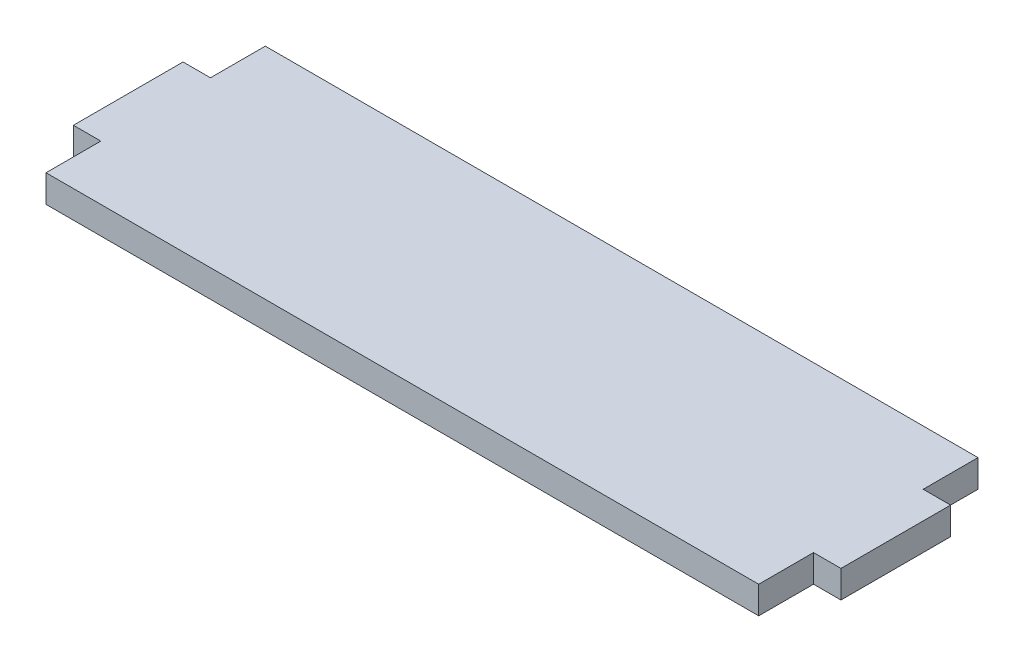
SolidWorks part; units mm, degrees
material "Balsa"
ref_plane "Front Plane" through (0, 0, 0) normal (0, 0, 1) x (1, 0, 0)
ref_plane "Top Plane" through (0, 0, 0) normal (0, 1, 0) x (1, 0, 0)
ref_plane "Right Plane" through (0, 0, 0) normal (1, 0, 0) x (0, 0, -1)
sketch "Sketch1" plane through (0, 0, 0) normal (0, 1, 0) x (1, 0, 0)
  line L0 (0, -12.7) -> (0, 12.7) construction
  line L1 (-41.275, 12.7) -> (41.275, 12.7)
  line L2 (41.275, 12.7) -> (41.275, 6.35)
  line L3 (41.275, 6.35) -> (44.45, 6.35)
  line L4 (44.45, 6.35) -> (44.45, -6.35)
  line L5 (44.45, -6.35) -> (41.275, -6.35)
  line L6 (41.275, -6.35) -> (41.275, -12.7)
  line L7 (41.275, -12.7) -> (-41.275, -12.7)
  line L8 (-41.275, -6.35) -> (-41.275, -12.7)
  line L9 (-44.45, -6.35) -> (-41.275, -6.35)
  line L10 (-44.45, 6.35) -> (-44.45, -6.35)
  line L11 (-41.275, 12.7) -> (-41.275, 6.35)
  line L12 (-41.275, 6.35) -> (-44.45, 6.35)
  point P0 (44.45, 0)
  point P4 (0, 0)
  dimension "1" = 25.4
  dimension "D2" = 12.7
  dimension "D3" = 44.45
  dimension "D4" = 3.175
extrude "Boss-Extrude1" add sketch "Sketch1" along normal blind 3.175
